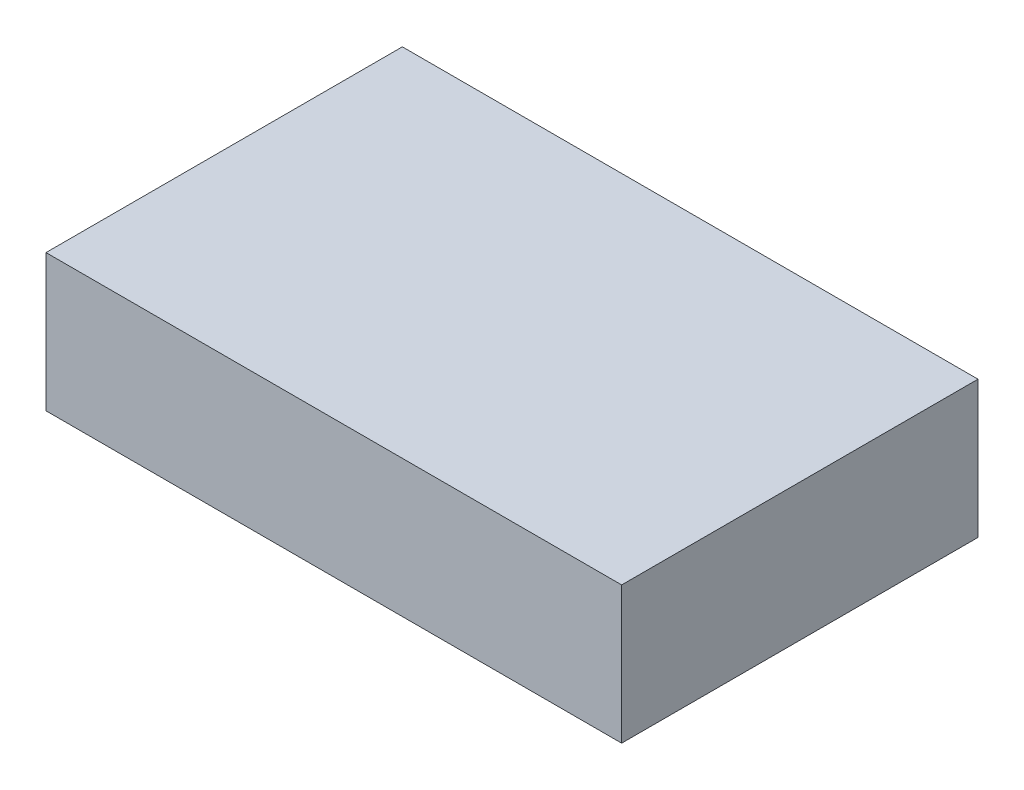
SolidWorks part; units mm, degrees
ref_plane "前视基准面" through (0, 0, 0) normal (0, 0, 1) x (1, 0, 0)
ref_plane "上视基准面" through (0, 0, 0) normal (0, 1, 0) x (1, 0, 0)
ref_plane "右视基准面" through (0, 0, 0) normal (1, 0, 0) x (0, 0, -1)
sketch "草图1" plane through (0, 0, 0) normal (0, 1, 0) x (1, 0, 0)
  line L1 (-21, 13) -> (21, 13)
  line L2 (-21, 13) -> (-21, -13)
  line L3 (-21, -13) -> (21, -13)
  line L4 (21, 13) -> (21, -13)
  line L5 (-21, 13) -> (21, -13) construction
  line L6 (-21, -13) -> (21, 13) construction
  point P0 (0, 0)
  dimension "D1" = 42
  dimension "D2" = 26
extrude "凸台-拉伸1" add sketch "草图1" along normal blind 10
